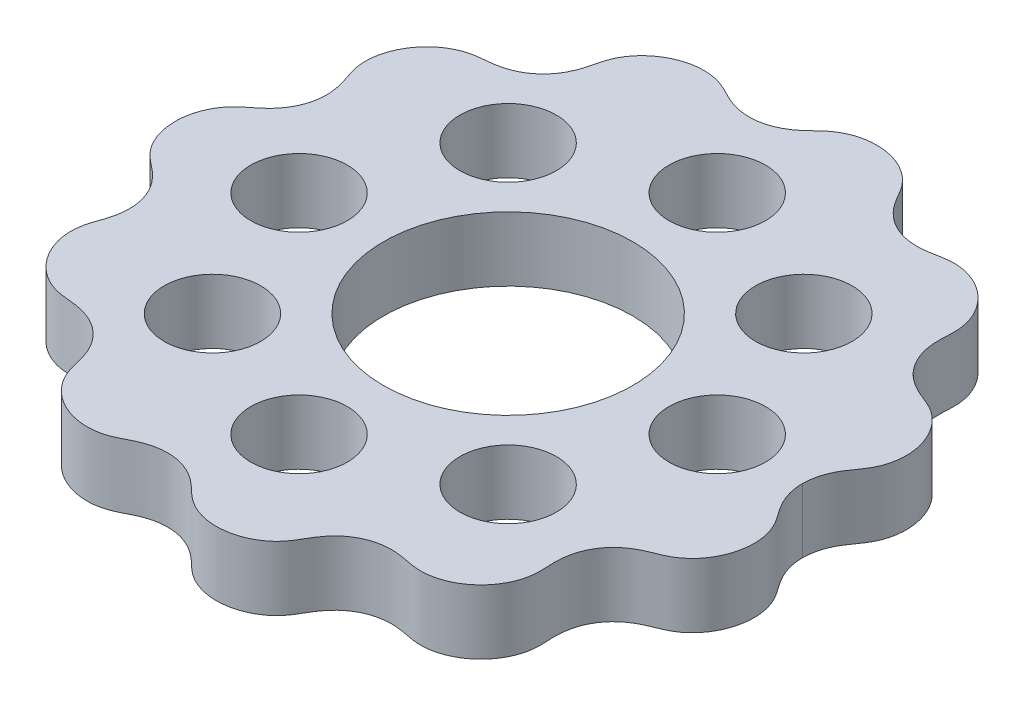
SolidWorks part; units mm, degrees
ref_plane "Front Plane" through (0, 0, 0) normal (0, 0, 1) x (1, 0, 0)
ref_plane "Top Plane" through (0, 0, 0) normal (0, 1, 0) x (1, 0, 0)
ref_plane "Right Plane" through (0, 0, 0) normal (1, 0, 0) x (0, 0, -1)
sketch "Sketch3" plane through (0, 0, 0) normal (0, 1, 0) x (1, 0, 0)
  line L0 (-30.6051, 0) -> (34.7487, 0) construction
  line L1 (0, 0) -> (0, 29.2445) construction
  spline S0 degree 4 poles (11.6189, 16.5432) (11.8178, 16.5149) (12.2108, 16.4276) (12.9492, 16.1436) (13.746, 15.5555) (14.3617, 14.7904) (14.7236, 13.9501) (14.8612, 13.2918) (14.865, 12.6715) (14.8197, 12.1053) (14.83, 11.5815) (14.8956, 11.1092) (15.007, 10.6932) (15.1452, 10.3349) (15.3154, 10.0076) (15.511, 9.7126) (15.7246, 9.4508) (15.9525, 9.2201) (16.1975, 9.0122) (16.4653, 8.8248) (16.7029, 8.6844) (16.9312, 8.5703) (17.1246, 8.4809) (17.3959, 8.3693) (17.5318, 8.3168) (17.8356, 8.1923) (18.031, 8.0988) (18.2545, 7.9769) (18.4535, 7.8462) (18.6983, 7.6613) (18.9517, 7.427) (19.209, 7.1339) (19.4525, 6.7789) (19.6486, 6.416) (19.8087, 6.0265) (19.9293, 5.6134) (20.0053, 5.1807) (20.0322, 4.7331) (20.0052, 4.2575) (19.9105, 3.7618) (19.734, 3.2584) (19.4598, 2.7684) (19.1286, 2.3294) (18.8254, 1.8814) (18.5806, 1.4078) (18.4064, 0.9137) (18.2839, 0.2821) (18.2883, -0.4839) (18.4665, -1.1796) (18.761, -1.77) (19.0269, -2.1778) (19.2109, -2.4357) (19.3957, -2.6929) (19.5656, -2.9607) (19.7479, -3.3127) (19.9386, -3.8341) (20.0574, -4.5402) (20.0084, -5.4053) (19.7399, -6.2999) (19.3164, -7.0355) (18.8045, -7.5977) (18.2523, -8.0019) (17.7028, -8.2583) (17.046, -8.4959) (16.3381, -8.8646) (15.6539, -9.4505) (15.1112, -10.2886) (14.8757, -11.08) (14.8227, -11.7251) (14.8331, -12.2747) (14.8653, -12.7277) (14.8627, -13.2601) (14.7284, -13.933) (14.4312, -14.6359) (13.9398, -15.3293) (13.2393, -15.9473) (12.4754, -16.3531) (11.7867, -16.5408) (11.2352, -16.5867) (10.8405, -16.5694) (10.5271, -16.5278) (10.2173, -16.4674) (9.9074, -16.4068) (9.4278, -16.3326) (8.7706, -16.3058) (7.9522, -16.4462) (7.0575, -16.8866) (6.3973, -17.4923) (5.9486, -18.142) (5.6247, -18.753) (5.2858, -19.2492) (4.8047, -19.7257) (4.176, -20.14) (3.4024, -20.4398) (2.5087, -20.57) (1.6927, -20.5039) (0.9916, -20.296) (0.4189, -19.998) (-0.0273, -19.6575) (-0.4146, -19.2674) (-0.8145, -18.9035) (-1.248, -18.5935) (-1.7119, -18.3505) (-2.3194, -18.1387) (-3.0782, -18.0333) (-3.7924, -18.11) (-4.4191, -18.3171) (-4.861, -18.5221) (-5.1425, -18.6675) (-5.4235, -18.8139) (-5.7127, -18.9442) (-6.0871, -19.0749) (-6.6306, -19.1899) (-7.3467, -19.2073) (-8.1962, -19.036) (-9.0436, -18.6432) (-9.7116, -18.1198) (-10.1953, -17.5335) (-10.5171, -16.93) (-10.6931, -16.3498) (-10.8346, -15.6663) (-11.0981, -14.9129) (-11.5802, -14.1521) (-12.3327, -13.4935) (-13.154, -13.1159) (-13.9425, -12.956) (-14.6452, -12.9123) (-15.2508, -12.8226) (-15.8975, -12.5902) (-16.5474, -12.1958) (-17.16, -11.6117) (-17.6691, -10.8344) (-17.9616, -10.0228) (-18.0497, -9.3149) (-18.017, -8.7626) (-17.9441, -8.3745) (-17.8585, -8.0703) (-17.7548, -7.7723) (-17.6507, -7.4743) (-17.5088, -7.0104) (-17.3883, -6.3641) (-17.4099, -5.5341) (-17.7175, -4.5856) (-18.2225, -3.8453) (-18.8015, -3.308) (-19.3605, -2.9003) (-19.8039, -2.4944) (-20.2076, -1.9504) (-20.5288, -1.269) (-20.7158, -0.4605) (-20.7178, 0.4427) (-20.5366, 1.2408) (-20.2316, 1.9051) (-19.8556, 2.4296) (-19.4556, 2.8229) (-19.0146, 3.1507) (-18.5974, 3.4944) (-18.2288, 3.8789) (-17.9219, 4.3031) (-17.6253, 4.8739) (-17.4121, 5.6098) (-17.3857, 6.3278) (-17.501, 6.9779) (-17.6409, 7.4447) (-17.7447, 7.7443) (-17.8497, 8.0433) (-17.9378, 8.3482) (-18.0142, 8.7375) (-18.051, 9.292) (-17.9667, 10.0036) (-17.6765, 10.8204) (-17.1675, 11.6035) (-16.5546, 12.1903) (-15.906, 12.5859) (-15.2632, 12.8188) (-14.6642, 12.9109) (-13.9676, 12.9536) (-13.185, 13.1065) (-12.3627, 13.4746) (-11.6037, 14.1249) (-11.1111, 14.8837) (-10.8676, 15.5695) (-10.7424, 16.1072) (-10.6331, 16.5515) (-10.4857, 16.9859) (-10.2015, 17.5258) (-9.7176, 18.1133) (-9.0531, 18.6371) (-8.2109, 19.0306) (-7.3665, 19.205) (-6.6533, 19.1918) (-6.1116, 19.0813) (-5.7378, 18.9541) (-5.4489, 18.8264) (-5.1688, 18.6814) (-4.8888, 18.536) (-4.4501, 18.3294) (-3.8279, 18.1177) (-3.0036, 18.0202) (-2.0208, 18.1887) (-1.2156, 18.5825) (-0.6007, 19.0789) (-0.1174, 19.5743) (0.3474, 19.956) (0.9434, 20.2787) (1.6637, 20.5001) (2.4907, 20.5705) (3.385, 20.4443) (4.1492, 20.1518) (4.7633, 19.7558) (5.229, 19.3095) (5.5616, 18.8581) (5.8234, 18.3752) (6.1038, 17.9134) (6.4315, 17.4937) (6.8071, 17.1293) (7.2217, 16.8315) (7.6634, 16.6034) (8.1203, 16.4444) (8.5815, 16.3511) (9.0507, 16.319) (9.4616, 16.3412) (9.8101, 16.3903) (10.0986, 16.4439) (10.3282, 16.4895) (10.5311, 16.526) (10.7049, 16.5505) (10.8484, 16.5653) (10.9716, 16.5733) (11.0921, 16.577) (11.1677, 16.5774) (11.2594, 16.5751) (11.3499, 16.5709) (11.4367, 16.5647) (11.5194, 16.5564) (11.6217, 16.5435) (11.7453, 16.524) (11.889, 16.4956) (12.0913, 16.4453) (12.3305, 16.3702) (12.602, 16.2618) (12.9005, 16.1114) (13.1849, 15.9359) (13.4773, 15.7195) (13.7698, 15.4569) (14.0541, 15.1433) (14.3167, 14.7752) (14.5534, 14.3454) (14.7409, 13.8521) (14.8591, 13.2967) (14.8673, 12.6928) (14.8104, 11.9996) (14.8464, 11.2056) (15.0918, 10.3263) (15.5701, 9.57) (16.1316, 9.0373) (16.5735, 8.7549) (16.8048, 8.6327) (16.9225, 8.5759) knots 0 0 0 0 0 0.005432 0.010864 0.021228 0.026411 0.031594 0.035438 0.039283 0.043127 0.046971 0.049563 0.052156 0.054748 0.057341 0.059524 0.061707 0.06389 0.066073 0.068256 0.070439 0.07153 0.072622 0.074805 0.076449 0.078093 0.079737 0.081382 0.083026 0.08467 0.087958 0.090741 0.093524 0.096307 0.09909 0.102115 0.105141 0.108166 0.111192 0.114971 0.11875 0.122529 0.126307 0.129839 0.133371 0.136903 0.140435 0.147176 0.153918 0.15606 0.158202 0.160344 0.162486 0.164628 0.16677 0.171054 0.177448 0.183843 0.189974 0.196106 0.20019 0.204275 0.20836 0.212445 0.219092 0.225739 0.23241 0.239081 0.24113 0.243178 0.247276 0.251373 0.255471 0.261622 0.267773 0.274148 0.280522 0.284792 0.286927 0.289062 0.291197 0.293332 0.295467 0.297602 0.304323 0.311044 0.317625 0.324205 0.32825 0.332295 0.33634 0.340384 0.346455 0.352526 0.358575 0.364624 0.368401 0.372178 0.375955 0.379732 0.383263 0.386793 0.390324 0.393854 0.400599 0.407343 0.409486 0.411628 0.413771 0.415914 0.418057 0.4202 0.424485 0.430883 0.43728 0.443409 0.449537 0.453621 0.457704 0.461787 0.465871 0.472515 0.479159 0.485846 0.492533 0.496656 0.50078 0.504903 0.509026 0.515118 0.52121 0.527582 0.533954 0.538222 0.540357 0.542491 0.544625 0.546759 0.548893 0.551027 0.557745 0.564464 0.571047 0.57763 0.581676 0.585723 0.589769 0.593816 0.59989 0.605963 0.612009 0.618055 0.621831 0.625606 0.629382 0.633157 0.636687 0.640216 0.643745 0.647274 0.654021 0.660768 0.662911 0.665055 0.667199 0.669342 0.671486 0.67363 0.677917 0.684317 0.690717 0.696843 0.702969 0.707051 0.711133 0.715214 0.719296 0.725937 0.732578 0.739268 0.745958 0.750083 0.752145 0.754208 0.758333 0.762458 0.768552 0.774647 0.781016 0.787386 0.791652 0.793786 0.795919 0.798052 0.800186 0.802319 0.804452 0.811168 0.817883 0.824469 0.831054 0.835103 0.839151 0.843199 0.847248 0.853324 0.8594 0.865444 0.871487 0.875261 0.879035 0.882809 0.886583 0.89011 0.893638 0.897166 0.900694 0.903866 0.907039 0.910211 0.913384 0.916556 0.918143 0.919729 0.921315 0.922901 0.923694 0.924488 0.925281 0.926074 0.926638 0.927203 0.927767 0.928331 0.928896 0.92946 0.930589 0.931717 0.932846 0.935103 0.937361 0.939618 0.941875 0.944133 0.947186 0.95024 0.953293 0.956347 0.960414 0.964482 0.968549 0.972617 0.979237 0.985858 0.992929 0.996465 1 1 1 1 1 construction
  spline S1 degree 4 poles (18.3, 0) (18.3, -0.215) (18.3388, -0.6792) (18.4818, -1.2103) (18.761, -1.77) (19.0269, -2.1778) (19.2109, -2.4357) (19.3957, -2.6929) (19.5656, -2.9607) (19.7479, -3.3127) (19.9386, -3.8341) (20.0574, -4.5402) (20.0084, -5.4053) (19.7399, -6.2999) (19.3164, -7.0355) (18.8045, -7.5977) (18.2523, -8.0019) (17.7028, -8.2583) (17.046, -8.4959) (16.3381, -8.8646) (15.6539, -9.4505) (15.1112, -10.2886) (14.8757, -11.08) (14.8227, -11.7251) (14.8331, -12.2747) (14.8653, -12.7277) (14.8627, -13.2601) (14.7284, -13.933) (14.4312, -14.6359) (13.9398, -15.3293) (13.2393, -15.9473) (12.4754, -16.3531) (11.7867, -16.5408) (11.2352, -16.5867) (10.8405, -16.5694) (10.5271, -16.5278) (10.2173, -16.4674) (9.9074, -16.4068) (9.4278, -16.3326) (8.7706, -16.3058) (7.9522, -16.4462) (7.0575, -16.8866) (6.3973, -17.4923) (5.9486, -18.142) (5.6247, -18.753) (5.2858, -19.2492) (4.8047, -19.7257) (4.176, -20.14) (3.4024, -20.4398) (2.5087, -20.57) (1.6927, -20.5039) (0.9916, -20.296) (0.4189, -19.998) (-0.0273, -19.6575) (-0.4146, -19.2674) (-0.8145, -18.9035) (-1.248, -18.5935) (-1.7119, -18.3505) (-2.3194, -18.1387) (-3.0782, -18.0333) (-3.7924, -18.11) (-4.4191, -18.3171) (-4.861, -18.5221) (-5.1425, -18.6675) (-5.4235, -18.8139) (-5.7127, -18.9442) (-6.0871, -19.0749) (-6.6306, -19.1899) (-7.3467, -19.2073) (-8.1962, -19.036) (-9.0436, -18.6432) (-9.7116, -18.1198) (-10.1953, -17.5335) (-10.5171, -16.93) (-10.6931, -16.3498) (-10.8346, -15.6663) (-11.0981, -14.9129) (-11.5802, -14.1521) (-12.3327, -13.4935) (-13.154, -13.1159) (-13.9425, -12.956) (-14.6452, -12.9123) (-15.2508, -12.8226) (-15.8975, -12.5902) (-16.5474, -12.1958) (-17.16, -11.6117) (-17.6691, -10.8344) (-17.9616, -10.0228) (-18.0497, -9.3149) (-18.017, -8.7626) (-17.9441, -8.3745) (-17.8585, -8.0703) (-17.7548, -7.7723) (-17.6507, -7.4743) (-17.5088, -7.0104) (-17.3883, -6.3641) (-17.4099, -5.5341) (-17.7175, -4.5856) (-18.2225, -3.8453) (-18.8015, -3.308) (-19.3605, -2.9003) (-19.8039, -2.4944) (-20.2076, -1.9504) (-20.5295, -1.2674) (-20.6657, -0.677) (-20.7, -0.2262) (-20.7, 0) knots 0.14136 0.14136 0.14136 0.14136 0.14136 0.147176 0.153918 0.15606 0.158202 0.160344 0.162486 0.164628 0.16677 0.171054 0.177448 0.183843 0.189974 0.196106 0.20019 0.204275 0.20836 0.212445 0.219092 0.225739 0.23241 0.239081 0.24113 0.243178 0.247276 0.251373 0.255471 0.261622 0.267773 0.274148 0.280522 0.284792 0.286927 0.289062 0.291197 0.293332 0.295467 0.297602 0.304323 0.311044 0.317625 0.324205 0.32825 0.332295 0.33634 0.340384 0.346455 0.352526 0.358575 0.364624 0.368401 0.372178 0.375955 0.379732 0.383263 0.386793 0.390324 0.393854 0.400599 0.407343 0.409486 0.411628 0.413771 0.415914 0.418057 0.4202 0.424485 0.430883 0.43728 0.443409 0.449537 0.453621 0.457704 0.461787 0.465871 0.472515 0.479159 0.485846 0.492533 0.496656 0.50078 0.504903 0.509026 0.515118 0.52121 0.527582 0.533954 0.538222 0.540357 0.542491 0.544625 0.546759 0.548893 0.551027 0.557745 0.564464 0.571047 0.57763 0.581676 0.585723 0.589769 0.593816 0.59989 0.60601 0.60601 0.60601 0.60601 0.60601
  spline S2 degree 4 poles (18.3, 0) (18.3, 0.215) (18.3388, 0.6792) (18.4818, 1.2103) (18.761, 1.77) (19.0269, 2.1778) (19.2109, 2.4357) (19.3957, 2.6929) (19.5656, 2.9607) (19.7479, 3.3127) (19.9386, 3.8341) (20.0574, 4.5402) (20.0084, 5.4053) (19.7399, 6.2999) (19.3164, 7.0355) (18.8045, 7.5977) (18.2523, 8.0019) (17.7028, 8.2583) (17.046, 8.4959) (16.3381, 8.8646) (15.6539, 9.4505) (15.1112, 10.2886) (14.8757, 11.08) (14.8227, 11.7251) (14.8331, 12.2747) (14.8653, 12.7277) (14.8627, 13.2601) (14.7284, 13.933) (14.4312, 14.6359) (13.9398, 15.3293) (13.2393, 15.9473) (12.4754, 16.3531) (11.7867, 16.5408) (11.2352, 16.5867) (10.8405, 16.5694) (10.5271, 16.5278) (10.2173, 16.4674) (9.9074, 16.4068) (9.4278, 16.3326) (8.7706, 16.3058) (7.9522, 16.4462) (7.0575, 16.8866) (6.3973, 17.4923) (5.9486, 18.142) (5.6247, 18.753) (5.2858, 19.2492) (4.8047, 19.7257) (4.176, 20.14) (3.4024, 20.4398) (2.5087, 20.57) (1.6927, 20.5039) (0.9916, 20.296) (0.4189, 19.998) (-0.0273, 19.6575) (-0.4146, 19.2674) (-0.8145, 18.9035) (-1.248, 18.5935) (-1.7119, 18.3505) (-2.3194, 18.1387) (-3.0782, 18.0333) (-3.7924, 18.11) (-4.4191, 18.3171) (-4.861, 18.5221) (-5.1425, 18.6675) (-5.4235, 18.8139) (-5.7127, 18.9442) (-6.0871, 19.0749) (-6.6306, 19.1899) (-7.3467, 19.2073) (-8.1962, 19.036) (-9.0436, 18.6432) (-9.7116, 18.1198) (-10.1953, 17.5335) (-10.5171, 16.93) (-10.6931, 16.3498) (-10.8346, 15.6663) (-11.0981, 14.9129) (-11.5802, 14.1521) (-12.3327, 13.4935) (-13.154, 13.1159) (-13.9425, 12.956) (-14.6452, 12.9123) (-15.2508, 12.8226) (-15.8975, 12.5902) (-16.5474, 12.1958) (-17.16, 11.6117) (-17.6691, 10.8344) (-17.9616, 10.0228) (-18.0497, 9.3149) (-18.017, 8.7626) (-17.9441, 8.3745) (-17.8585, 8.0703) (-17.7548, 7.7723) (-17.6507, 7.4743) (-17.5088, 7.0104) (-17.3883, 6.3641) (-17.4099, 5.5341) (-17.7175, 4.5856) (-18.2225, 3.8453) (-18.8015, 3.308) (-19.3605, 2.9003) (-19.8039, 2.4944) (-20.2076, 1.9504) (-20.5295, 1.2674) (-20.6657, 0.677) (-20.7, 0.2262) (-20.7, 0) knots 0.14136 0.14136 0.14136 0.14136 0.14136 0.147176 0.153918 0.15606 0.158202 0.160344 0.162486 0.164628 0.16677 0.171054 0.177448 0.183843 0.189974 0.196106 0.20019 0.204275 0.20836 0.212445 0.219092 0.225739 0.23241 0.239081 0.24113 0.243178 0.247276 0.251373 0.255471 0.261622 0.267773 0.274148 0.280522 0.284792 0.286927 0.289062 0.291197 0.293332 0.295467 0.297602 0.304323 0.311044 0.317625 0.324205 0.32825 0.332295 0.33634 0.340384 0.346455 0.352526 0.358575 0.364624 0.368401 0.372178 0.375955 0.379732 0.383263 0.386793 0.390324 0.393854 0.400599 0.407343 0.409486 0.411628 0.413771 0.415914 0.418057 0.4202 0.424485 0.430883 0.43728 0.443409 0.449537 0.453621 0.457704 0.461787 0.465871 0.472515 0.479159 0.485846 0.492533 0.496656 0.50078 0.504903 0.509026 0.515118 0.52121 0.527582 0.533954 0.538222 0.540357 0.542491 0.544625 0.546759 0.548893 0.551027 0.557745 0.564464 0.571047 0.57763 0.581676 0.585723 0.589769 0.593816 0.59989 0.60601 0.60601 0.60601 0.60601 0.60601
sketch "Sketch4" plane through (0, 0, 0) normal (0, 1, 0) x (1, 0, 0)
  line L0 (-200030.6051, 0) -> (200034.7487, 0) construction
  circle A0 centre (0, 0) radius 7.75
  circle A1 centre (0, 0) radius 13 construction
  circle A2 centre (-13, 0) radius 3
  circle A3 centre (-9.1924, 9.1924) radius 3
  circle A4 centre (0, 13) radius 3
  circle A5 centre (9.1924, 9.1924) radius 3
  circle A6 centre (13, 0) radius 3
  circle A7 centre (9.1924, -9.1924) radius 3
  circle A8 centre (0, -13) radius 3
  circle A9 centre (-9.1924, -9.1924) radius 3
  dimension "D2" = 15.5
  dimension "D1" = 6
  dimension "D3" = 26
  dimension "D4" = 8
sketch "Sketch5" plane through (0, 0, 0) normal (0, 1, 0) x (1, 0, 0)
  circle A0 centre (0, 0) radius 7.75 construction
  circle A1 centre (-9.1924, -9.1924) radius 3 construction
  circle A2 centre (0, -13) radius 3 construction
  circle A3 centre (9.1924, -9.1924) radius 3 construction
  circle A4 centre (13, 0) radius 3 construction
  circle A5 centre (9.1924, 9.1924) radius 3 construction
  circle A6 centre (0, 13) radius 3 construction
  circle A7 centre (-9.1924, 9.1924) radius 3 construction
  circle A8 centre (-13, 0) radius 3 construction
  circle A9 centre (0, 0) radius 7.75
  circle A10 centre (-9.1924, -9.1924) radius 3
  circle A11 centre (0, -13) radius 3
  circle A12 centre (9.1924, -9.1924) radius 3
  circle A13 centre (13, 0) radius 3
  circle A14 centre (9.1924, 9.1924) radius 3
  circle A15 centre (0, 13) radius 3
  circle A16 centre (-9.1924, 9.1924) radius 3
  circle A17 centre (-13, 0) radius 3
  spline S0 degree 4 poles (-1809.2513, 807.2819) (146.7121, 76.7471) (36.4943, -24.6981) (14.8431, -6.0839) (18.761, 1.77) (19.0269, 2.1778) (19.2109, 2.4357) (19.3957, 2.6929) (19.5656, 2.9607) (19.7479, 3.3127) (19.9386, 3.8341) (20.0574, 4.5402) (20.0084, 5.4053) (19.7399, 6.2999) (19.3164, 7.0355) (18.8045, 7.5977) (18.2523, 8.0019) (17.7028, 8.2583) (17.046, 8.4959) (16.3381, 8.8646) (15.6539, 9.4505) (15.1112, 10.2886) (14.8757, 11.08) (14.8227, 11.7251) (14.8331, 12.2747) (14.8653, 12.7277) (14.8627, 13.2601) (14.7284, 13.933) (14.4312, 14.6359) (13.9398, 15.3293) (13.2393, 15.9473) (12.4754, 16.3531) (11.7867, 16.5408) (11.2352, 16.5867) (10.8405, 16.5694) (10.5271, 16.5278) (10.2173, 16.4674) (9.9074, 16.4068) (9.4278, 16.3326) (8.7706, 16.3058) (7.9522, 16.4462) (7.0575, 16.8866) (6.3973, 17.4923) (5.9486, 18.142) (5.6247, 18.753) (5.2858, 19.2492) (4.8047, 19.7257) (4.176, 20.14) (3.4024, 20.4398) (2.5087, 20.57) (1.6927, 20.5039) (0.9916, 20.296) (0.4189, 19.998) (-0.0273, 19.6575) (-0.4146, 19.2674) (-0.8145, 18.9035) (-1.248, 18.5935) (-1.7119, 18.3505) (-2.3194, 18.1387) (-3.0782, 18.0333) (-3.7924, 18.11) (-4.4191, 18.3171) (-4.861, 18.5221) (-5.1425, 18.6675) (-5.4235, 18.8139) (-5.7127, 18.9442) (-6.0871, 19.0749) (-6.6306, 19.1899) (-7.3467, 19.2073) (-8.1962, 19.036) (-9.0436, 18.6432) (-9.7116, 18.1198) (-10.1953, 17.5335) (-10.5171, 16.93) (-10.6931, 16.3498) (-10.8346, 15.6663) (-11.0981, 14.9129) (-11.5802, 14.1521) (-12.3327, 13.4935) (-13.154, 13.1159) (-13.9425, 12.956) (-14.6452, 12.9123) (-15.2508, 12.8226) (-15.8975, 12.5902) (-16.5474, 12.1958) (-17.16, 11.6117) (-17.6691, 10.8344) (-17.9616, 10.0228) (-18.0497, 9.3149) (-18.017, 8.7626) (-17.9441, 8.3745) (-17.8585, 8.0703) (-17.7548, 7.7723) (-17.6507, 7.4743) (-17.5088, 7.0104) (-17.3883, 6.3641) (-17.4099, 5.5341) (-17.7175, 4.5856) (-18.2225, 3.8453) (-18.8015, 3.308) (-19.3605, 2.9003) (-19.8039, 2.4944) (-20.2076, 1.9504) (-25.8227, -9.9631) (24.986, -42.0648) (120.8284, 301.3247) (1015.9721, -1697.7457) knots -0.078152 -0.078152 -0.078152 -0.078152 -0.078152 0.147176 0.153918 0.15606 0.158202 0.160344 0.162486 0.164628 0.16677 0.171054 0.177448 0.183843 0.189974 0.196106 0.20019 0.204275 0.20836 0.212445 0.219092 0.225739 0.23241 0.239081 0.24113 0.243178 0.247276 0.251373 0.255471 0.261622 0.267773 0.274148 0.280522 0.284792 0.286927 0.289062 0.291197 0.293332 0.295467 0.297602 0.304323 0.311044 0.317625 0.324205 0.32825 0.332295 0.33634 0.340384 0.346455 0.352526 0.358575 0.364624 0.368401 0.372178 0.375955 0.379732 0.383263 0.386793 0.390324 0.393854 0.400599 0.407343 0.409486 0.411628 0.413771 0.415914 0.418057 0.4202 0.424485 0.430883 0.43728 0.443409 0.449537 0.453621 0.457704 0.461787 0.465871 0.472515 0.479159 0.485846 0.492533 0.496656 0.50078 0.504903 0.509026 0.515118 0.52121 0.527582 0.533954 0.538222 0.540357 0.542491 0.544625 0.546759 0.548893 0.551027 0.557745 0.564464 0.571047 0.57763 0.581676 0.585723 0.589769 0.593816 0.59989 0.939627 0.939627 0.939627 0.939627 0.939627 only from (18.3, 0) to (-20.7, 0) construction
  spline S1 degree 4 poles (-1809.2513, -807.2819) (146.7121, -76.7471) (36.4943, 24.6981) (14.8431, 6.0839) (18.761, -1.77) (19.0269, -2.1778) (19.2109, -2.4357) (19.3957, -2.6929) (19.5656, -2.9607) (19.7479, -3.3127) (19.9386, -3.8341) (20.0574, -4.5402) (20.0084, -5.4053) (19.7399, -6.2999) (19.3164, -7.0355) (18.8045, -7.5977) (18.2523, -8.0019) (17.7028, -8.2583) (17.046, -8.4959) (16.3381, -8.8646) (15.6539, -9.4505) (15.1112, -10.2886) (14.8757, -11.08) (14.8227, -11.7251) (14.8331, -12.2747) (14.8653, -12.7277) (14.8627, -13.2601) (14.7284, -13.933) (14.4312, -14.6359) (13.9398, -15.3293) (13.2393, -15.9473) (12.4754, -16.3531) (11.7867, -16.5408) (11.2352, -16.5867) (10.8405, -16.5694) (10.5271, -16.5278) (10.2173, -16.4674) (9.9074, -16.4068) (9.4278, -16.3326) (8.7706, -16.3058) (7.9522, -16.4462) (7.0575, -16.8866) (6.3973, -17.4923) (5.9486, -18.142) (5.6247, -18.753) (5.2858, -19.2492) (4.8047, -19.7257) (4.176, -20.14) (3.4024, -20.4398) (2.5087, -20.57) (1.6927, -20.5039) (0.9916, -20.296) (0.4189, -19.998) (-0.0273, -19.6575) (-0.4146, -19.2674) (-0.8145, -18.9035) (-1.248, -18.5935) (-1.7119, -18.3505) (-2.3194, -18.1387) (-3.0782, -18.0333) (-3.7924, -18.11) (-4.4191, -18.3171) (-4.861, -18.5221) (-5.1425, -18.6675) (-5.4235, -18.8139) (-5.7127, -18.9442) (-6.0871, -19.0749) (-6.6306, -19.1899) (-7.3467, -19.2073) (-8.1962, -19.036) (-9.0436, -18.6432) (-9.7116, -18.1198) (-10.1953, -17.5335) (-10.5171, -16.93) (-10.6931, -16.3498) (-10.8346, -15.6663) (-11.0981, -14.9129) (-11.5802, -14.1521) (-12.3327, -13.4935) (-13.154, -13.1159) (-13.9425, -12.956) (-14.6452, -12.9123) (-15.2508, -12.8226) (-15.8975, -12.5902) (-16.5474, -12.1958) (-17.16, -11.6117) (-17.6691, -10.8344) (-17.9616, -10.0228) (-18.0497, -9.3149) (-18.017, -8.7626) (-17.9441, -8.3745) (-17.8585, -8.0703) (-17.7548, -7.7723) (-17.6507, -7.4743) (-17.5088, -7.0104) (-17.3883, -6.3641) (-17.4099, -5.5341) (-17.7175, -4.5856) (-18.2225, -3.8453) (-18.8015, -3.308) (-19.3605, -2.9003) (-19.8039, -2.4944) (-20.2076, -1.9504) (-25.8227, 9.9631) (24.986, 42.0648) (120.8284, -301.3247) (1015.9722, 1697.7457) knots -0.078152 -0.078152 -0.078152 -0.078152 -0.078152 0.147176 0.153918 0.15606 0.158202 0.160344 0.162486 0.164628 0.16677 0.171054 0.177448 0.183843 0.189974 0.196106 0.20019 0.204275 0.20836 0.212445 0.219092 0.225739 0.23241 0.239081 0.24113 0.243178 0.247276 0.251373 0.255471 0.261622 0.267773 0.274148 0.280522 0.284792 0.286927 0.289062 0.291197 0.293332 0.295467 0.297602 0.304323 0.311044 0.317625 0.324205 0.32825 0.332295 0.33634 0.340384 0.346455 0.352526 0.358575 0.364624 0.368401 0.372178 0.375955 0.379732 0.383263 0.386793 0.390324 0.393854 0.400599 0.407343 0.409486 0.411628 0.413771 0.415914 0.418057 0.4202 0.424485 0.430883 0.43728 0.443409 0.449537 0.453621 0.457704 0.461787 0.465871 0.472515 0.479159 0.485846 0.492533 0.496656 0.50078 0.504903 0.509026 0.515118 0.52121 0.527582 0.533954 0.538222 0.540357 0.542491 0.544625 0.546759 0.548893 0.551027 0.557745 0.564464 0.571047 0.57763 0.581676 0.585723 0.589769 0.593816 0.59989 0.939627 0.939627 0.939627 0.939627 0.939627 only from (18.3, 0) to (-20.7, 0) construction
  spline S2 degree 4 poles (18.3, 0) (18.3, 0.215) (18.3388, 0.6792) (18.4818, 1.2103) (18.761, 1.77) (19.0269, 2.1778) (19.2109, 2.4357) (19.3957, 2.6929) (19.5656, 2.9607) (19.7479, 3.3127) (19.9386, 3.8341) (20.0574, 4.5402) (20.0084, 5.4053) (19.7399, 6.2999) (19.3164, 7.0355) (18.8045, 7.5977) (18.2523, 8.0019) (17.7028, 8.2583) (17.046, 8.4959) (16.3381, 8.8646) (15.6539, 9.4505) (15.1112, 10.2886) (14.8757, 11.08) (14.8227, 11.7251) (14.8331, 12.2747) (14.8653, 12.7277) (14.8627, 13.2601) (14.7284, 13.933) (14.4312, 14.6359) (13.9398, 15.3293) (13.2393, 15.9473) (12.4754, 16.3531) (11.7867, 16.5408) (11.2352, 16.5867) (10.8405, 16.5694) (10.5271, 16.5278) (10.2173, 16.4674) (9.9074, 16.4068) (9.4278, 16.3326) (8.7706, 16.3058) (7.9522, 16.4462) (7.0575, 16.8866) (6.3973, 17.4923) (5.9486, 18.142) (5.6247, 18.753) (5.2858, 19.2492) (4.8047, 19.7257) (4.176, 20.14) (3.4024, 20.4398) (2.5087, 20.57) (1.6927, 20.5039) (0.9916, 20.296) (0.4189, 19.998) (-0.0273, 19.6575) (-0.4146, 19.2674) (-0.8145, 18.9035) (-1.248, 18.5935) (-1.7119, 18.3505) (-2.3194, 18.1387) (-3.0782, 18.0333) (-3.7924, 18.11) (-4.4191, 18.3171) (-4.861, 18.5221) (-5.1425, 18.6675) (-5.4235, 18.8139) (-5.7127, 18.9442) (-6.0871, 19.0749) (-6.6306, 19.1899) (-7.3467, 19.2073) (-8.1962, 19.036) (-9.0436, 18.6432) (-9.7116, 18.1198) (-10.1953, 17.5335) (-10.5171, 16.93) (-10.6931, 16.3498) (-10.8346, 15.6663) (-11.0981, 14.9129) (-11.5802, 14.1521) (-12.3327, 13.4935) (-13.154, 13.1159) (-13.9425, 12.956) (-14.6452, 12.9123) (-15.2508, 12.8226) (-15.8975, 12.5902) (-16.5474, 12.1958) (-17.16, 11.6117) (-17.6691, 10.8344) (-17.9616, 10.0228) (-18.0497, 9.3149) (-18.017, 8.7626) (-17.9441, 8.3745) (-17.8585, 8.0703) (-17.7548, 7.7723) (-17.6507, 7.4743) (-17.5088, 7.0104) (-17.3883, 6.3641) (-17.4099, 5.5341) (-17.7175, 4.5856) (-18.2225, 3.8453) (-18.8015, 3.308) (-19.3605, 2.9003) (-19.8039, 2.4944) (-20.2076, 1.9504) (-20.5295, 1.2674) (-20.6657, 0.677) (-20.7, 0.2262) (-20.7, 0) knots 0.14136 0.14136 0.14136 0.14136 0.14136 0.147176 0.153918 0.15606 0.158202 0.160344 0.162486 0.164628 0.16677 0.171054 0.177448 0.183843 0.189974 0.196106 0.20019 0.204275 0.20836 0.212445 0.219092 0.225739 0.23241 0.239081 0.24113 0.243178 0.247276 0.251373 0.255471 0.261622 0.267773 0.274148 0.280522 0.284792 0.286927 0.289062 0.291197 0.293332 0.295467 0.297602 0.304323 0.311044 0.317625 0.324205 0.32825 0.332295 0.33634 0.340384 0.346455 0.352526 0.358575 0.364624 0.368401 0.372178 0.375955 0.379732 0.383263 0.386793 0.390324 0.393854 0.400599 0.407343 0.409486 0.411628 0.413771 0.415914 0.418057 0.4202 0.424485 0.430883 0.43728 0.443409 0.449537 0.453621 0.457704 0.461787 0.465871 0.472515 0.479159 0.485846 0.492533 0.496656 0.50078 0.504903 0.509026 0.515118 0.52121 0.527582 0.533954 0.538222 0.540357 0.542491 0.544625 0.546759 0.548893 0.551027 0.557745 0.564464 0.571047 0.57763 0.581676 0.585723 0.589769 0.593816 0.59989 0.60601 0.60601 0.60601 0.60601 0.60601
  spline S3 degree 4 poles (18.3, 0) (18.3, -0.215) (18.3388, -0.6792) (18.4818, -1.2103) (18.761, -1.77) (19.0269, -2.1778) (19.2109, -2.4357) (19.3957, -2.6929) (19.5656, -2.9607) (19.7479, -3.3127) (19.9386, -3.8341) (20.0574, -4.5402) (20.0084, -5.4053) (19.7399, -6.2999) (19.3164, -7.0355) (18.8045, -7.5977) (18.2523, -8.0019) (17.7028, -8.2583) (17.046, -8.4959) (16.3381, -8.8646) (15.6539, -9.4505) (15.1112, -10.2886) (14.8757, -11.08) (14.8227, -11.7251) (14.8331, -12.2747) (14.8653, -12.7277) (14.8627, -13.2601) (14.7284, -13.933) (14.4312, -14.6359) (13.9398, -15.3293) (13.2393, -15.9473) (12.4754, -16.3531) (11.7867, -16.5408) (11.2352, -16.5867) (10.8405, -16.5694) (10.5271, -16.5278) (10.2173, -16.4674) (9.9074, -16.4068) (9.4278, -16.3326) (8.7706, -16.3058) (7.9522, -16.4462) (7.0575, -16.8866) (6.3973, -17.4923) (5.9486, -18.142) (5.6247, -18.753) (5.2858, -19.2492) (4.8047, -19.7257) (4.176, -20.14) (3.4024, -20.4398) (2.5087, -20.57) (1.6927, -20.5039) (0.9916, -20.296) (0.4189, -19.998) (-0.0273, -19.6575) (-0.4146, -19.2674) (-0.8145, -18.9035) (-1.248, -18.5935) (-1.7119, -18.3505) (-2.3194, -18.1387) (-3.0782, -18.0333) (-3.7924, -18.11) (-4.4191, -18.3171) (-4.861, -18.5221) (-5.1425, -18.6675) (-5.4235, -18.8139) (-5.7127, -18.9442) (-6.0871, -19.0749) (-6.6306, -19.1899) (-7.3467, -19.2073) (-8.1962, -19.036) (-9.0436, -18.6432) (-9.7116, -18.1198) (-10.1953, -17.5335) (-10.5171, -16.93) (-10.6931, -16.3498) (-10.8346, -15.6663) (-11.0981, -14.9129) (-11.5802, -14.1521) (-12.3327, -13.4935) (-13.154, -13.1159) (-13.9425, -12.956) (-14.6452, -12.9123) (-15.2508, -12.8226) (-15.8975, -12.5902) (-16.5474, -12.1958) (-17.16, -11.6117) (-17.6691, -10.8344) (-17.9616, -10.0228) (-18.0497, -9.3149) (-18.017, -8.7626) (-17.9441, -8.3745) (-17.8585, -8.0703) (-17.7548, -7.7723) (-17.6507, -7.4743) (-17.5088, -7.0104) (-17.3883, -6.3641) (-17.4099, -5.5341) (-17.7175, -4.5856) (-18.2225, -3.8453) (-18.8015, -3.308) (-19.3605, -2.9003) (-19.8039, -2.4944) (-20.2076, -1.9504) (-20.5295, -1.2674) (-20.6657, -0.677) (-20.7, -0.2262) (-20.7, 0) knots 0.14136 0.14136 0.14136 0.14136 0.14136 0.147176 0.153918 0.15606 0.158202 0.160344 0.162486 0.164628 0.16677 0.171054 0.177448 0.183843 0.189974 0.196106 0.20019 0.204275 0.20836 0.212445 0.219092 0.225739 0.23241 0.239081 0.24113 0.243178 0.247276 0.251373 0.255471 0.261622 0.267773 0.274148 0.280522 0.284792 0.286927 0.289062 0.291197 0.293332 0.295467 0.297602 0.304323 0.311044 0.317625 0.324205 0.32825 0.332295 0.33634 0.340384 0.346455 0.352526 0.358575 0.364624 0.368401 0.372178 0.375955 0.379732 0.383263 0.386793 0.390324 0.393854 0.400599 0.407343 0.409486 0.411628 0.413771 0.415914 0.418057 0.4202 0.424485 0.430883 0.43728 0.443409 0.449537 0.453621 0.457704 0.461787 0.465871 0.472515 0.479159 0.485846 0.492533 0.496656 0.50078 0.504903 0.509026 0.515118 0.52121 0.527582 0.533954 0.538222 0.540357 0.542491 0.544625 0.546759 0.548893 0.551027 0.557745 0.564464 0.571047 0.57763 0.581676 0.585723 0.589769 0.593816 0.59989 0.60601 0.60601 0.60601 0.60601 0.60601
extrude "Boss-Extrude1" add sketch "Sketch5" along normal blind 4
